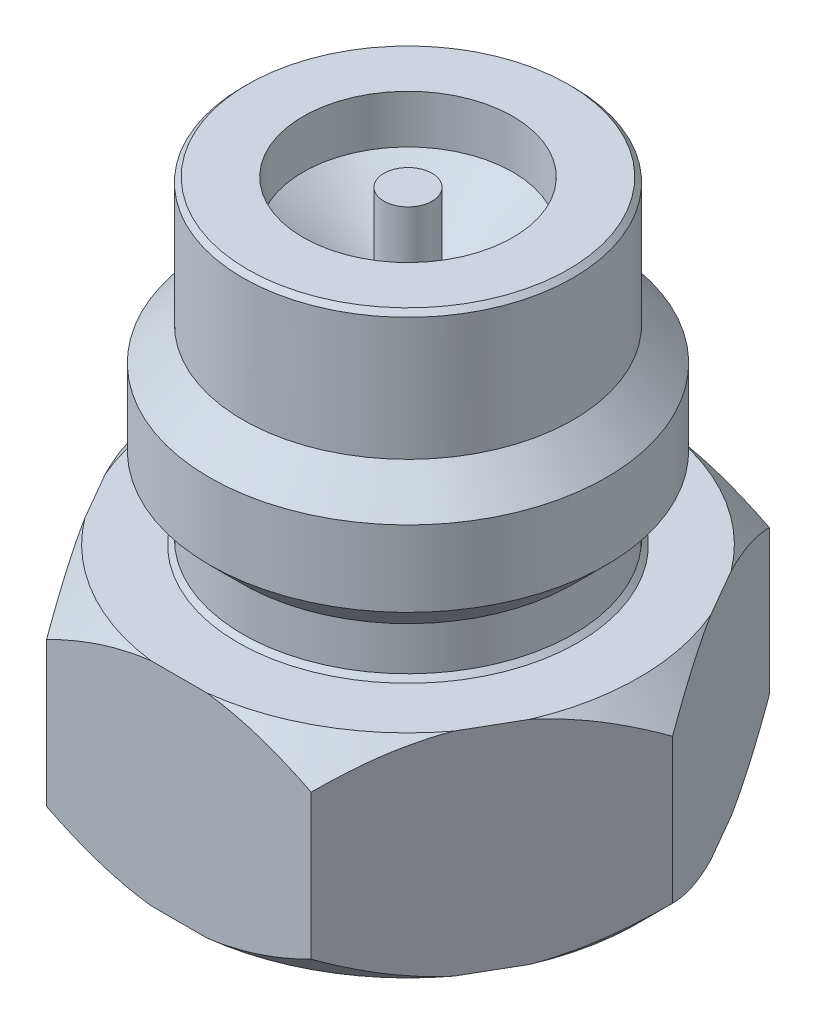
SolidWorks part; units mm, degrees
material "Brass"
ref_plane "Front Plane" through (0, 0, 0) normal (0, 0, 1) x (1, 0, 0)
ref_plane "Top Plane" through (0, 0, 0) normal (0, 1, 0) x (1, 0, 0)
ref_plane "Right Plane" through (0, 0, 0) normal (1, 0, 0) x (0, 0, -1)
sketch "Sketch2" plane through (0, 0, 0) normal (0, 0, 1) x (1, 0, 0)
  line L0 (0, 0) -> (0, 16.2941)
  line L1 (0, 16.2941) -> (1.27, 16.2941)
  line L2 (1.27, 16.2941) -> (1.27, 11.2141)
  line L3 (1.27, 11.2141) -> (5.5245, 14.224)
  line L4 (5.5245, 14.224) -> (5.5245, 16.764)
  line L5 (5.5245, 16.764) -> (8.6995, 16.764)
  line L6 (8.6995, 16.764) -> (8.6995, 10.033)
  line L7 (8.6995, 10.033) -> (10.4521, 8.2804)
  line L8 (10.4521, 8.2804) -> (10.4521, 4.2926)
  line L9 (10.4521, 4.2926) -> (8.6995, 2.54)
  line L10 (8.6995, 2.54) -> (8.6995, 0)
  line L11 (8.6995, 0) -> (0, 0)
  point P12 (1.27, 32.7722)
  dimension "D1" = 8.6995
  dimension "D2" = 135
  dimension "D3" = 3.175
  dimension "D4" = 1.27
  dimension "D5" = 2.54
  dimension "D6" = 5.08
  dimension "D7" = 0.4699
  dimension "D8" = 16.764
  dimension "D9" = 10.4521
  dimension "D10" = 2.54
  dimension "D11" = 6.731
revolve "Revolve1" add sketch "Sketch2" angle 360 about L0
sketch "Sketch3" plane through (0, 0, 0) normal (0, -1, 0) x (1, 0, 0)
  line L1 (13.9315, 0) -> (6.9657, 12.065)
  line L2 (6.9657, 12.065) -> (-6.9657, 12.065)
  line L3 (-6.9657, 12.065) -> (-13.9315, 0)
  line L4 (-13.9315, 0) -> (-6.9657, -12.065)
  line L5 (-6.9657, -12.065) -> (6.9657, -12.065)
  line L6 (6.9657, -12.065) -> (13.9315, 0)
  circle A0 centre (0, 0) radius 12.065 construction
  dimension "D1" = 24.13
extrude "Boss-Extrude1" add sketch "Sketch3" along normal blind 11.176
sketch "Sketch5" plane through (0, 0, 0) normal (0, 0, 1) x (1, 0, 0)
  line L0 (12.1535, 0) -> (16.5897, 0)
  line L1 (13.9315, 0) -> (6.9657, 0) construction
  line L2 (16.5897, 0) -> (16.5897, -11.176)
  line L3 (16.5897, -11.176) -> (12.1535, -11.176)
  line L4 (13.9315, -11.176) -> (6.9657, -11.176) construction
  line L5 (12.1535, -11.176) -> (13.9315, -9.398)
  line L6 (13.9315, -11.176) -> (13.9315, 0) construction
  line L7 (13.9315, -9.398) -> (13.9315, -1.778)
  line L8 (13.9315, -1.778) -> (12.1535, 0)
  line L9 (0, 0) -> (0, -12.855) construction
  line L10 (13.9315, -1.778) -> (13.9315, -9.398)
  dimension "D1" = 45
  dimension "D2" = 1.778
revolve "Cut-Revolve1" cut sketch "Sketch5" angle 360 about L9
chamfer "Chamfer1" distance 0.254 angle 45 2 edges at (0, 16.764, -8.6995) (0, 0, -8.6995)
